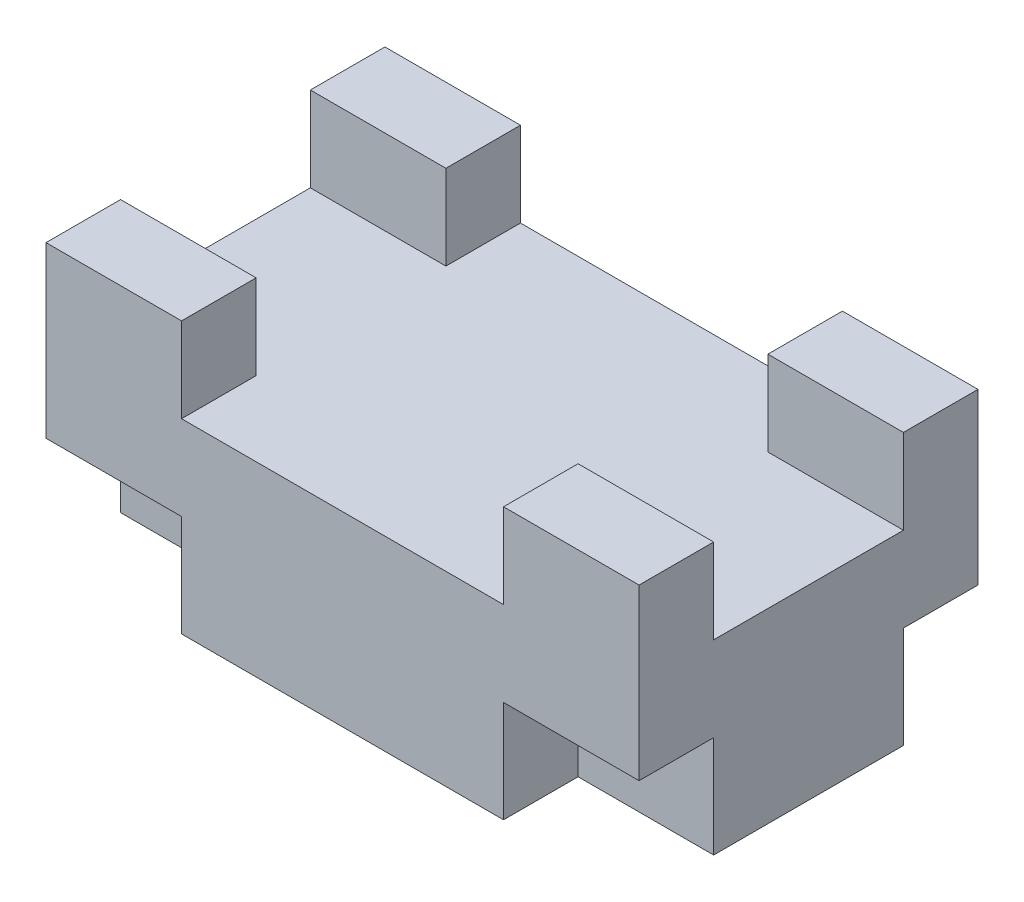
SolidWorks part; units mm, degrees
ref_plane "Front Plane" through (0, 0, 0) normal (0, 0, 1) x (1, 0, 0)
ref_plane "Top Plane" through (0, 0, 0) normal (0, 1, 0) x (1, 0, 0)
ref_plane "Right Plane" through (0, 0, 0) normal (1, 0, 0) x (0, 0, -1)
sketch "Sketch1" plane through (0, 0, 0) normal (0, 0, 1) x (1, 0, 0)
  line L1 (87.5, -40) -> (-87.5, -40)
  line L2 (87.5, -40) -> (87.5, 40)
  line L3 (87.5, 40) -> (-87.5, 40)
  line L4 (-87.5, -40) -> (-87.5, 40)
  line L5 (87.5, -40) -> (-87.5, 40) construction
  line L6 (87.5, 40) -> (-87.5, -40) construction
  point P0 (0, 0)
  dimension "D1" = 80
  dimension "D2" = 175
extrude "Boss-Extrude1" add sketch "Sketch1" along normal mid plane 100
sketch "Sketch2" plane through (0, 40, 0) normal (0, 1, 0) x (1, 0, 0)
  line L0 (87.5, 50) -> (-87.5, 50) construction
  line L1 (47.5, -50) -> (-47.5, -50)
  line L2 (47.5, -50) -> (47.5, -28)
  line L3 (47.5, 50) -> (-47.5, 50)
  line L4 (-47.5, -50) -> (-47.5, -28)
  line L5 (47.5, -50) -> (-47.5, 50) construction
  line L6 (47.5, 50) -> (-47.5, -50) construction
  line L7 (-87.5, -50) -> (-87.5, 50) construction
  line L8 (87.5, -28) -> (47.5, -28)
  line L9 (87.5, -28) -> (87.5, 28)
  line L10 (87.5, 28) -> (47.5, 28)
  line L11 (-87.5, -28) -> (-87.5, 28)
  line L12 (87.5, -28) -> (-87.5, 28) construction
  line L13 (87.5, 28) -> (-87.5, -28) construction
  line L14 (87.5, -50) -> (87.5, 50) construction
  line L15 (-47.5, 28) -> (-87.5, 28)
  line L16 (47.5, 28) -> (47.5, 50)
  line L17 (-47.5, -28) -> (-87.5, -28)
  line L18 (-47.5, 28) -> (-47.5, 50)
  point P0 (0, 0)
  point P8 (0, 0)
  dimension "D1" = 22
  dimension "D2" = 40
extrude "Cut-Extrude1" cut sketch "Sketch2" against normal blind 25
sketch "Sketch3" plane through (0, -40, 0) normal (0, -1, 0) x (1, 0, 0)
  line L1 (87.5, 50) -> (47.5, 50)
  line L2 (87.5, 50) -> (87.5, 28)
  line L3 (87.5, 28) -> (47.5, 28)
  line L4 (47.5, 50) -> (47.5, 28)
  dimension "D1" = 22
  dimension "D2" = 40
extrude "Cut-Extrude2" cut sketch "Sketch3" against normal blind 30
mirror "Mirror1" about plane through (0, 0, 0) normal (1, 0, 0) of "Cut-Extrude2" second plane through (0, 0, 0) second plane normal (0, 0, 1)
